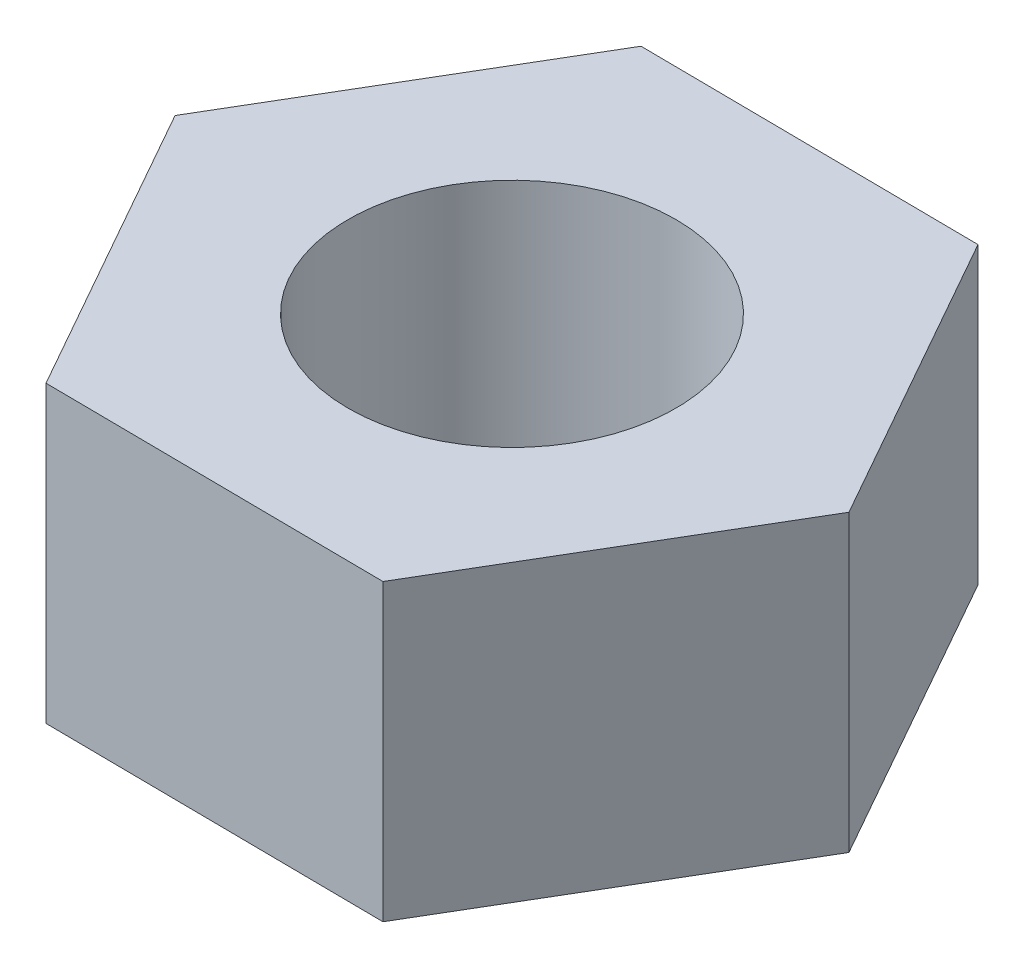
SolidWorks part; units mm, degrees
ref_plane "Płaszczyzna przednia" through (0, 0, 0) normal (0, 0, 1) x (1, 0, 0)
ref_plane "Płaszczyzna górna" through (0, 0, 0) normal (0, 1, 0) x (1, 0, 0)
ref_plane "Płaszczyzna prawa" through (0, 0, 0) normal (1, 0, 0) x (0, 0, -1)
sketch "Sketch1" plane through (0, 0, 0) normal (0, 1, 0) x (1, 0, 0)
  line L1 (2.6416, 4.4746) -> (-2.5543, 4.525)
  line L2 (-2.5543, 4.525) -> (-5.1959, 0.0504)
  line L3 (-5.1959, 0.0504) -> (-2.6416, -4.4746)
  line L4 (-2.6416, -4.4746) -> (2.5543, -4.525)
  line L5 (2.5543, -4.525) -> (5.1959, -0.0504)
  line L6 (5.1959, -0.0504) -> (2.6416, 4.4746)
  circle A0 centre (0, 0) radius 4.5 construction
  circle A1 centre (0, 0) radius 2.5
  dimension "D2" = 5
  dimension "D1" = 9
extrude "Boss-Extrude1" add sketch "Sketch1" along normal blind 4.5
